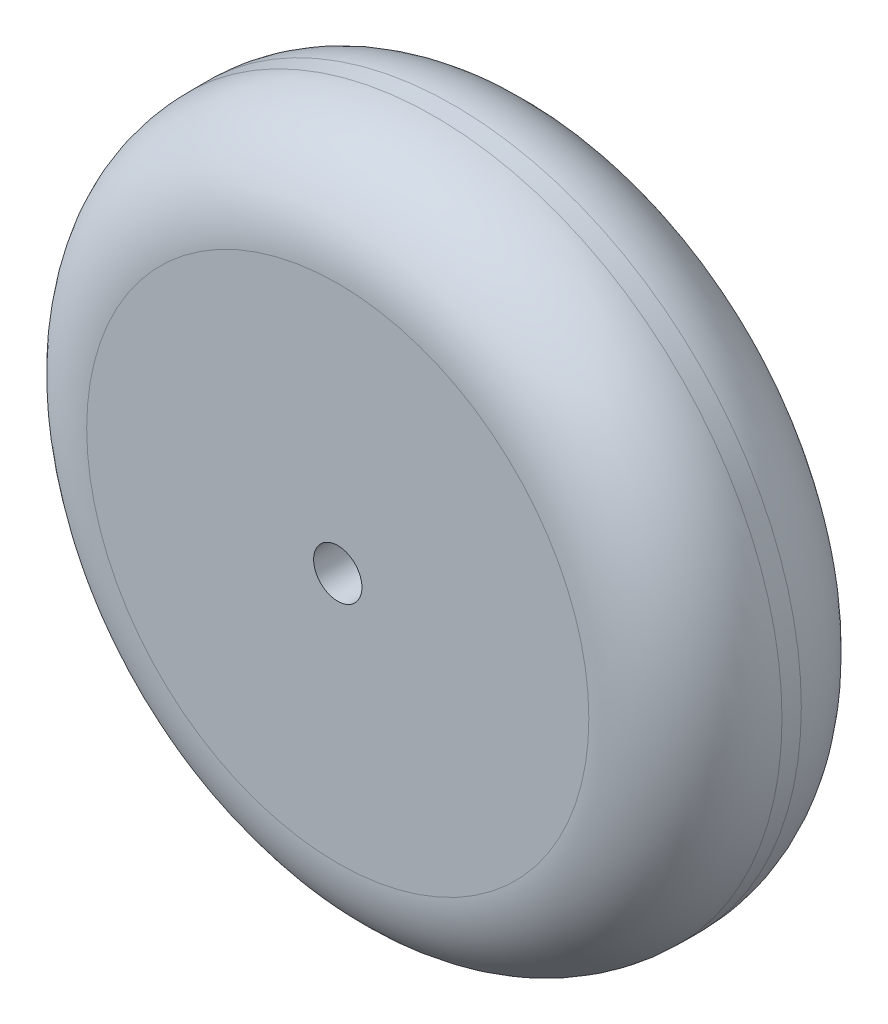
SolidWorks part; units mm, degrees
ref_plane "Front Plane" through (0, 0, 0) normal (0, 0, 1) x (1, 0, 0)
ref_plane "Top Plane" through (0, 0, 0) normal (0, 1, 0) x (1, 0, 0)
ref_plane "Right Plane" through (0, 0, 0) normal (1, 0, 0) x (0, 0, -1)
sketch "Sketch1" plane through (0, 0, 0) normal (0, 0, 1) x (1, 0, 0)
  circle A0 centre (0, 0) radius 36
  dimension "D1" = 72
extrude "Wheel-Base" add sketch "Sketch1" along normal blind 22
sketch "Sketch2" plane through (0, 0, 22) normal (0, 0, 1) x (1, 0, 0)
  circle A0 centre (0, 0) radius 2.5
  dimension "D1" = 5
extrude "Shaft-Hole" cut sketch "Sketch2" against normal through all
fillet "Rounding" radius 10 2 edges at (36, 0, 0) (36, 0, 22)
equation "\"Foamcore\" = .1in"
equation "\"MDF\" = .3in"
equation "\"Gmaterial\"= \"MDF\""
